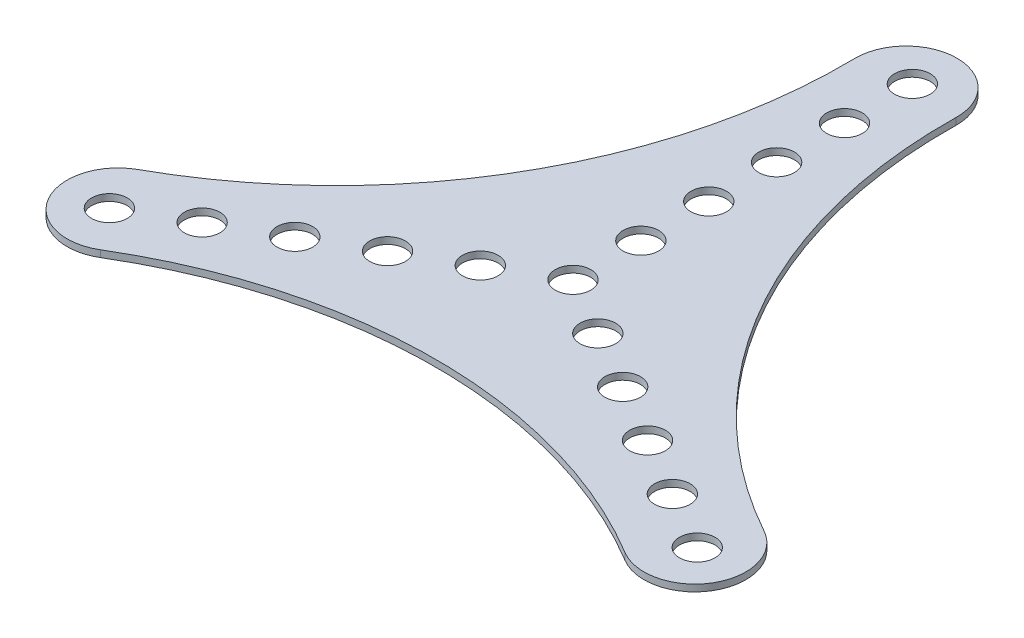
SolidWorks part; units mm, degrees
ref_plane "Front" through (0, 0, 0) normal (0, 0, 1) x (1, 0, 0)
ref_plane "Top" through (0, 0, 0) normal (0, 1, 0) x (1, 0, 0)
ref_plane "Right" through (0, 0, 0) normal (1, 0, 0) x (0, 0, -1)
sketch "Sketch1" plane through (0, 0, 0) normal (0, 1, 0) x (1, 0, 0)
  line L0 (100, -9.3938) -> (100, -52.9417) construction
  line L1 (-100, -19.5442) -> (-100, -52.9417) construction
  line L2 (0, 0) -> (85, -49.0748) construction
  line L3 (0, 0) -> (0, -113.1495) construction
  line L4 (-85, -49.0748) -> (0, 0) construction
  line L5 (0, 0) -> (0, 98.1495) construction
  circle A0 centre (0, 0) radius 113.1495 construction
  circle A1 centre (0, 0) radius 5.5 construction
  circle A2 centre (-85, -49.0748) radius 15
  circle A3 centre (0, 0) radius 15
  circle A4 centre (164.9745, 95.2481) radius 150
  circle A5 centre (-164.9745, 95.2481) radius 150
  circle A6 centre (85, -49.0748) radius 15
  circle A7 centre (0, -190.4961) radius 150
  circle A8 centre (0, 98.1495) radius 15
  circle A9 centre (-85, -49.0748) radius 5.5
  circle A10 centre (85, -49.0748) radius 5.5
  circle A11 centre (0, 98.1495) radius 5.5
  dimension "D1" = 200
  dimension "D3" = 11
  dimension "D4" = 30
  dimension "D5" = 11
  dimension "D6" = 300
  dimension "D7" = 120
  dimension "D2" = 100
extrude "Boss-Extrude1" add sketch "Sketch1" along normal mid plane 2 contours A8 A5 A2 A7 A6 A4 A3 | A2 | A6 | A3 | A8 | A11 | A9 | A10
sketch "Sketch2" plane through (0, 1, 0) normal (0, 1, 0) x (1, 0, 0)
  circle A0 centre (0, 0) radius 5.25
  dimension "D1" = 10.5
extrude "Cut-Extrude1" cut sketch "Sketch2" against normal up to next
sketch "Sketch3" plane through (0, 1, 0) normal (0, 1, 0) x (1, 0, 0)
  line L0 (0, 0) -> (0, 113.1495) construction
  line L1 (0, 0) -> (97.9904, -56.5748) construction
  line L2 (0, 0) -> (-97.9904, -56.5748) construction
  arc A0 (14.9977, 97.8858) -> (-14.9977, 97.8858) centre (0, 98.1495) ccw construction
  arc A2 (77.2727, -61.9313) -> (92.2704, -35.9545) centre (85, -49.0748) ccw construction
  arc A3 (-92.2704, -35.9545) -> (-77.2727, -61.9313) centre (-85, -49.0748) ccw construction
  dimension "D1" = 120
  dimension "D2" = 120
pattern_linear "LPattern1" count 6 spacing 20 along (0, 0, -1) of "Cut-Extrude1"
pattern_circular "CirPattern1" count 3 over 360 about axis through (0, 0, 0) along (0, 1, 0) of "LPattern1"
